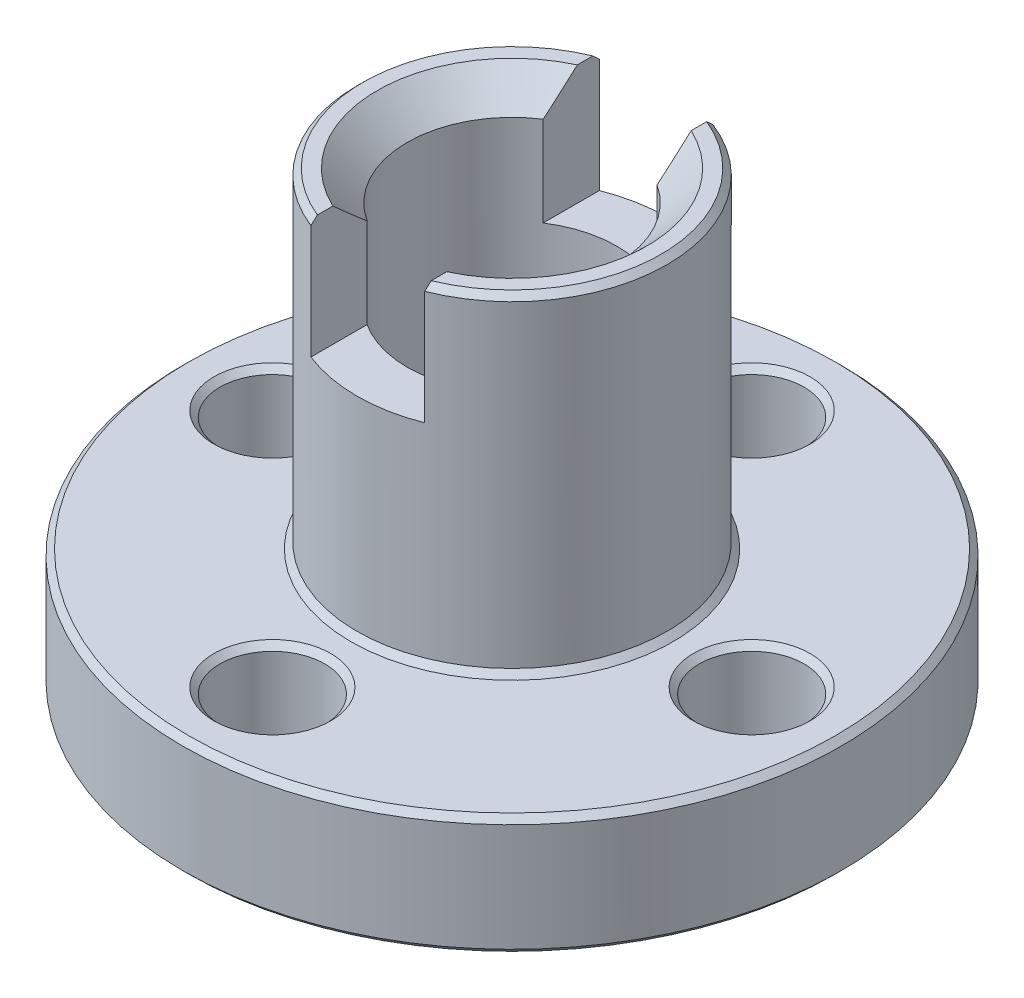
SolidWorks part; units mm, degrees
material "Латунь"
ref_plane "Спереди" through (0, 0, 0) normal (0, 0, 1) x (1, 0, 0)
ref_plane "Сверху" through (0, 0, 0) normal (0, 1, 0) x (1, 0, 0)
ref_plane "Справа" through (0, 0, 0) normal (1, 0, 0) x (0, 0, -1)
sketch "Эскиз2" plane through (0, 0, 0) normal (1, 0, 0) x (0, 0, -1)
  line L0 (0, 0) -> (11, 0)
  line L1 (11, 0) -> (11, 4)
  line L2 (11, 4) -> (5.175, 4)
  line L3 (5.175, 4) -> (5.175, 15)
  line L4 (5.175, 15) -> (0, 15)
  line L5 (0, 15) -> (0, 0)
  line L6 (0, 40.8158) -> (0, -22.7526) construction
  line L7 (3.5, 15) -> (3.5, 0)
  dimension "D1" = 22
  dimension "D2" = 4
  dimension "D3" = 10.35
  dimension "D4" = 15
  dimension "D5" = 7
revolve "Повернуть1" add sketch "Эскиз2" angle 360 about L6
sketch "Эскиз3" plane through (0, 0, 0) normal (0, 0, 1) x (1, 0, 0)
  line L0 (0, 16.2105) -> (0, -1.0118) construction
  line L1 (-1.9, 15) -> (1.9, 15)
  line L3 (5.175, 15) -> (-5.175, 15) construction
  line L4 (1.9, 15) -> (1.9, 11)
  line L5 (1.9, 11) -> (-1.9, 11)
  line L6 (-1.9, 11) -> (-1.9, 15)
  point P6 (0, 15)
  dimension "D1" = 3.8
  dimension "D2" = 4
extrude "Вырез-Вытянуть1" cut sketch "Эскиз3" against normal through all both and the other way through all
sketch "Эскиз4" plane through (0, 0, 0) normal (0, -1, 0) x (1, 0, 0)
  line L0 (0, 11.701) -> (0, -11.9582) construction
  circle A0 centre (0, 8) radius 1.75
  circle A1 centre (8, 0) radius 1.75
  circle A2 centre (0, -8) radius 1.75
  circle A3 centre (-8, 0) radius 1.75
  point P14 (0, 0)
  dimension "D2" = 3.5
  dimension "D1" = 8
  dimension "D3" = 4
extrude "Вырез-Вытянуть2" cut sketch "Эскиз4" against normal blind 4
chamfer "Фаска1" distance 1 angle 45 3 edges at (3.5, 15, 0) (-3.5, 15, 0) (0, 0, 3.5)
chamfer "Фаска2" distance 0.2 angle 45 13 edges at (0, 0, -9.75) (0, 4, -9.75) (8, 0, -1.75) (8, 4, -1.75) (-8, 0, -1.75) (-8, 4, -1.75) (0, 0, 6.25) (0, 4, 6.25) (0, 0, 11) (0, 4, 11) (0, 4, 5.175) (5.175, 15, 0) (-5.175, 15, 0)
